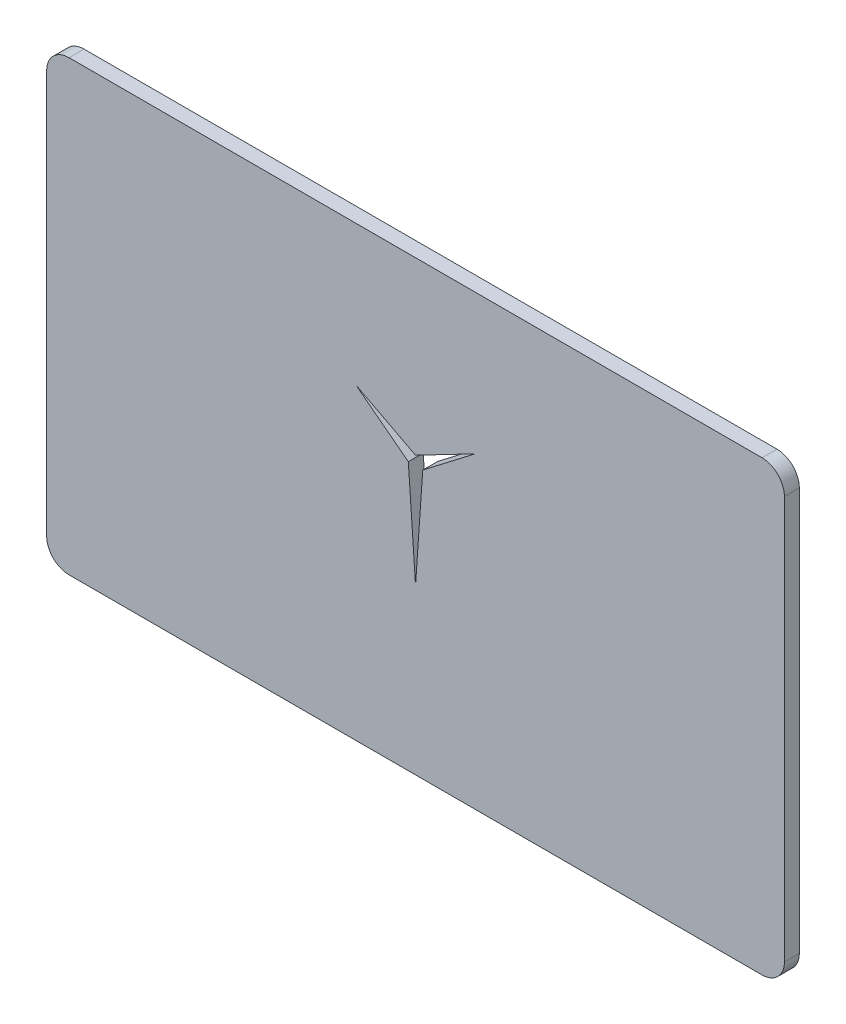
SolidWorks part; units mm, degrees
ref_plane "前视基准面" through (0, 0, 0) normal (0, 0, 1) x (1, 0, 0)
ref_plane "上视基准面" through (0, 0, 0) normal (0, 1, 0) x (1, 0, 0)
ref_plane "右视基准面" through (0, 0, 0) normal (1, 0, 0) x (0, 0, -1)
other "Configuration Table"
sketch "草图1" plane through (0, 0, 0) normal (0, 0, 1) x (1, 0, 0)
  line L0 (0, 30) -> (0, -30) construction
  line L1 (-46.4146, 30) -> (46.4146, 30)
  line L2 (-49.4146, 27) -> (-49.4146, -27)
  line L3 (-46.4146, -30) -> (46.4146, -30)
  line L4 (49.4146, 27) -> (49.4146, -27)
  line L5 (-49.4146, 30) -> (49.4146, -30) construction
  line L6 (-49.4146, -30) -> (49.4146, 30) construction
  line L7 (0, -8) -> (-0.9688, 5.8548)
  line L8 (0, -8) -> (0.9688, 5.8548)
  line L9 (-8, 11.2501) -> (-0.9688, 5.8548)
  line L10 (-8, 11.2501) -> (0, 7.0855)
  line L11 (8, 11.2501) -> (0.9688, 5.8548)
  line L12 (8, 11.2501) -> (0, 7.0855)
  circle A0 centre (0, 7) radius 1.5 construction
  arc A1 (46.4146, 30) -> (49.4146, 27) centre (46.4146, 27) cw
  arc A2 (-49.4146, -27) -> (-46.4146, -30) centre (-46.4146, -27) ccw
  arc A3 (-46.4146, 30) -> (-49.4146, 27) centre (-46.4146, 27) ccw
  arc A4 (46.4146, -30) -> (49.4146, -27) centre (46.4146, -27) ccw
  point P0 (0, 0)
  point P8 (0, 7)
  point P14 (0, 0)
  point P15 (0, 0)
  point P16 (13.1989, 14.6302)
  point P17 (0, 8)
  point P22 (0, 7)
  dimension "D4" = 3
  dimension "D10" = 3
  dimension "D1" = 60
  dimension "D2" = 98.8291
  dimension "D3" = 7
  dimension "D5" = 8
  dimension "D7" = 10
  dimension "D6" = 125
  dimension "D8" = 15
  dimension "D9" = 8
extrude "凸台-拉伸1" add sketch "草图1" along normal blind 2
